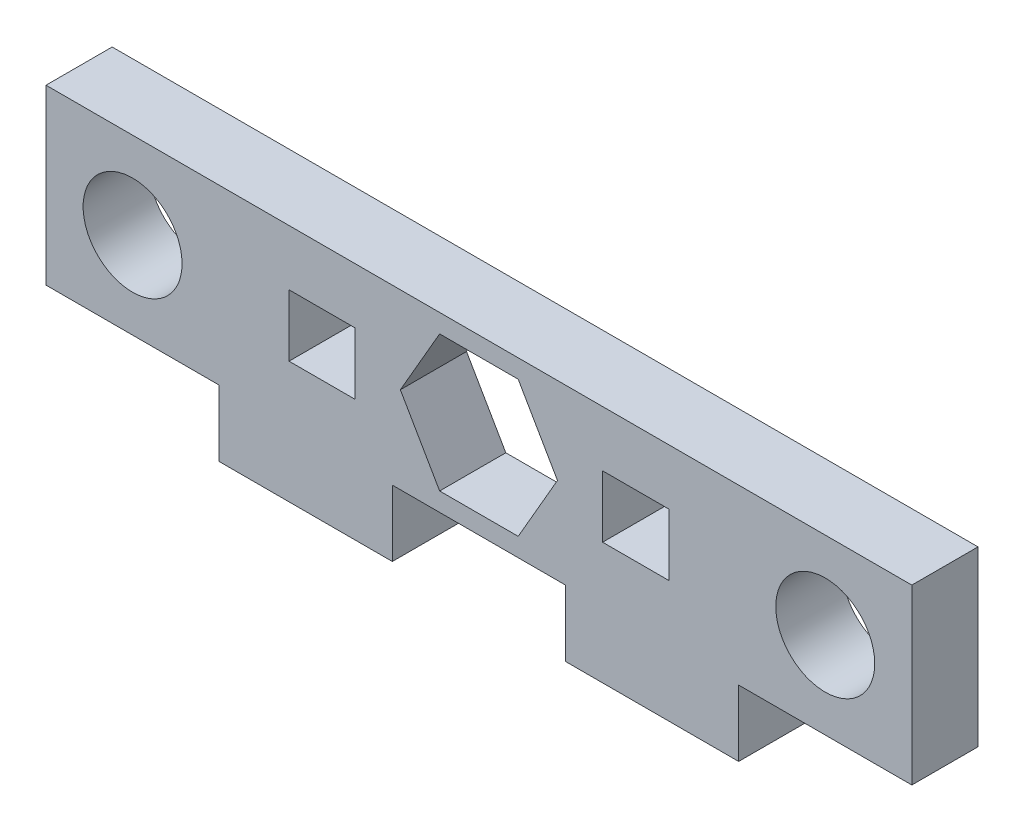
SolidWorks part; units mm, degrees
ref_plane "Front Plane" through (0, 0, 0) normal (0, 0, 1) x (1, 0, 0)
ref_plane "Top Plane" through (0, 0, 0) normal (0, 1, 0) x (1, 0, 0)
ref_plane "Right Plane" through (0, 0, 0) normal (1, 0, 0) x (0, 0, -1)
sketch "Model" plane through (0, 0, 0) normal (0, 0, 1) x (1, 0, 0)
  line L442 (45, 14.85) -> (45, 9.85)
  line L443 (45, 9.85) -> (50.35, 9.85)
  line L444 (50.35, 9.85) -> (50.35, 14.85)
  line L445 (50.35, 14.85) -> (45, 14.85)
  line L446 (25, 9.85) -> (25, 14.85)
  line L447 (25, 14.85) -> (19.65, 14.85)
  line L448 (19.65, 14.85) -> (19.65, 9.85)
  line L449 (19.65, 9.85) -> (25, 9.85)
  line L450 (70, 5.35) -> (70, 19.35)
  line L451 (56, 5.35) -> (70, 5.35)
  line L452 (56, 0) -> (56, 5.35)
  line L453 (42, 0) -> (56, 0)
  line L454 (42, 5.35) -> (42, 0)
  line L455 (28, 5.35) -> (42, 5.35)
  line L456 (28, 0) -> (28, 5.35)
  line L457 (14, 0) -> (28, 0)
  line L458 (14, 5.35) -> (14, 0)
  line L459 (0, 5.35) -> (14, 5.35)
  line L460 (0, 19.35) -> (0, 5.35)
  line L461 (70, 19.35) -> (0, 19.35)
  line L462 (41.3509, 12.35) -> (38.1754, 17.85)
  line L463 (38.1754, 17.85) -> (31.8246, 17.85)
  line L464 (31.8246, 17.85) -> (28.6491, 12.35)
  line L465 (28.6491, 12.35) -> (31.8246, 6.85)
  line L466 (31.8246, 6.85) -> (38.1754, 6.85)
  line L467 (38.1754, 6.85) -> (41.3509, 12.35)
  circle A48 centre (7, 12.35) radius 4
  circle A49 centre (63, 12.35) radius 4
extrude "Boss-Extrude1" add sketch "Model" along normal blind 5.35
